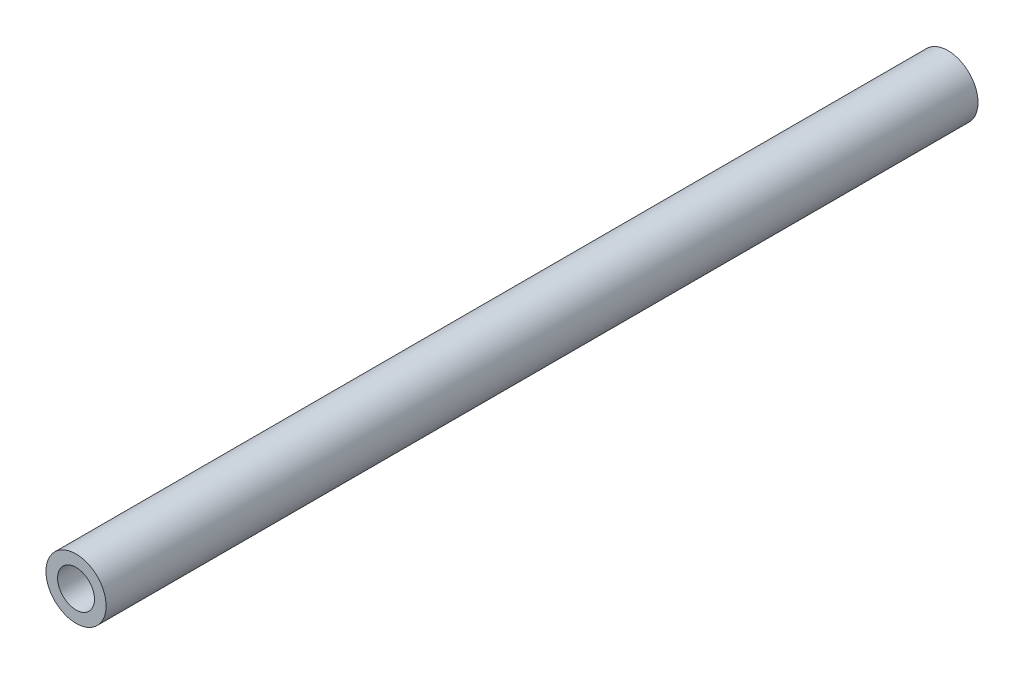
SolidWorks part; units mm, degrees
material "Polieter Polyol"
ref_plane "Ön Düzlem" through (0, 0, 0) normal (0, 0, 1) x (1, 0, 0)
ref_plane "Üst Düzlem" through (0, 0, 0) normal (0, 1, 0) x (1, 0, 0)
ref_plane "Sağ Düzlem" through (0, 0, 0) normal (1, 0, 0) x (0, 0, -1)
sketch "Çizim1" plane through (0, 0, 0) normal (0, 0, 1) x (1, 0, 0)
  circle A0 centre (0, 0) radius 10.35
  circle A1 centre (0, 0) radius 6.35
  dimension "D1" = 20.7
  dimension "D2" = 12.7
extrude "Yükseklik-Ekstrüzyon1" add sketch "Çizim1" along normal blind 300
